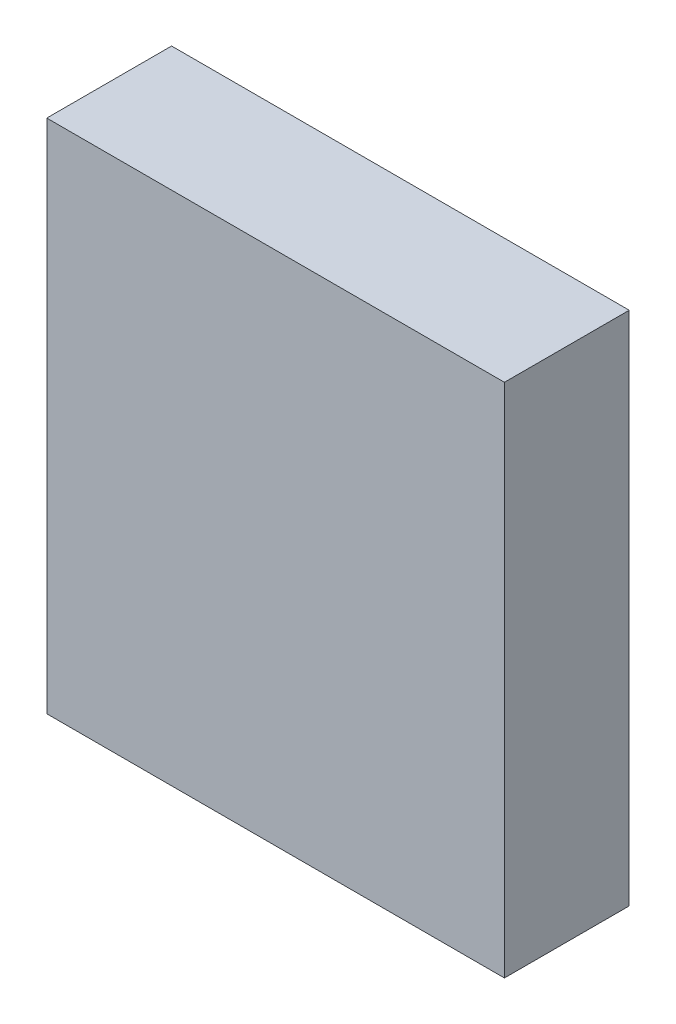
SolidWorks part; units mm, degrees
ref_plane "Plan de face" through (0, 0, 0) normal (0, 0, 1) x (1, 0, 0)
ref_plane "Plan de dessus" through (0, 0, 0) normal (0, 1, 0) x (1, 0, 0)
ref_plane "Plan de droite" through (0, 0, 0) normal (1, 0, 0) x (0, 0, -1)
sketch "Esquisse1" plane through (0, 0, 0) normal (0, 0, 1) x (1, 0, 0)
  line L1 (-21.1299, 9.4774) -> (33.8701, 9.4774)
  line L2 (-21.1299, 9.4774) -> (-21.1299, -52.5226)
  line L3 (-21.1299, -52.5226) -> (33.8701, -52.5226)
  line L4 (33.8701, 9.4774) -> (33.8701, -52.5226)
  dimension "D1" = 55
  dimension "D2" = 62
extrude "Boss.-Extru.1" add sketch "Esquisse1" along normal blind 15
